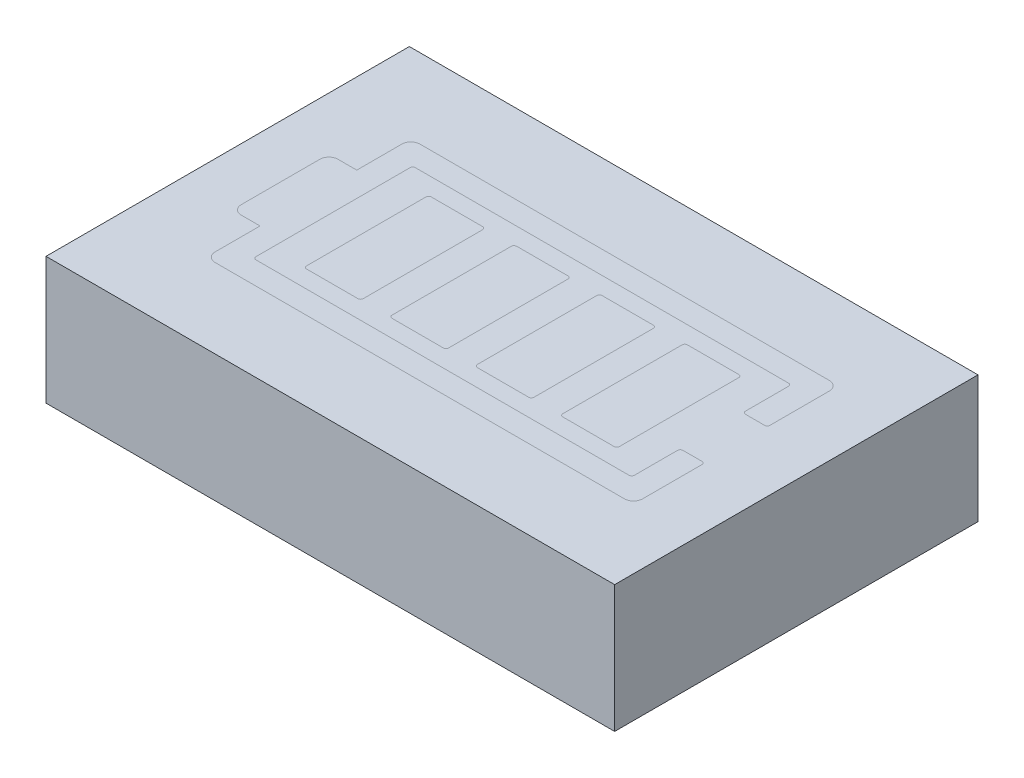
SolidWorks part; units mm, degrees
ref_plane "Front Plane" through (0, 0, 0) normal (0, 0, 1) x (1, 0, 0)
ref_plane "Top Plane" through (0, 0, 0) normal (0, 1, 0) x (1, 0, 0)
ref_plane "Right Plane" through (0, 0, 0) normal (1, 0, 0) x (0, 0, -1)
sketch "Sketch1" plane through (0, 0, 0) normal (0, 1, 0) x (1, 0, 0)
  line L0 (-14.65, -9) -> (-14.65, 9)
  line L1 (-15.65, -10) -> (15.65, -10)
  line L2 (-15.65, -10) -> (-15.65, 10)
  line L3 (-15.65, 10) -> (15.65, 10)
  line L4 (15.65, -10) -> (15.65, 10)
  line L5 (-15.65, -10) -> (15.65, 10) construction
  line L6 (-15.65, 10) -> (15.65, -10) construction
  line L7 (-14.65, 9) -> (-7, 9)
  line L8 (14.65, -9) -> (14.65, 9)
  line L9 (-14.65, -9) -> (-7, -9)
  line L10 (-7, 7) -> (-6, 7)
  line L12 (-7, 9) -> (-7, 7)
  line L14 (-6, 9) -> (-6, 7)
  line L15 (-7, 9) -> (-6.8889, 7) construction
  line L16 (-7, -9) -> (-6.8889, -7) construction
  line L17 (0, -9) -> (0, 9) construction
  line L18 (-14.65, 0) -> (14.65, 0) construction
  line L19 (-7, -7) -> (-6, -7)
  line L20 (-7, -7) -> (-7, -9)
  line L21 (-6.1111, -7) -> (-6, -9) construction
  line L22 (-6.1111, 7) -> (-6, 9) construction
  line L23 (-6, -7) -> (-6, -9)
  line L24 (-6, 9) -> (6, 9)
  line L25 (-14.65, 9) -> (14.65, 9) construction
  line L26 (-6, -9) -> (6, -9)
  line L27 (-14.65, -9) -> (14.65, -9) construction
  line L28 (6.1111, -7) -> (6, -9) construction
  line L29 (7, -9) -> (6.8889, -7) construction
  line L30 (6, -7) -> (6, -9)
  line L31 (7, -7) -> (7, -9)
  line L32 (7, -7) -> (6, -7)
  line L33 (6.1111, 7) -> (6, 9) construction
  line L34 (7, 9) -> (6.8889, 7) construction
  line L35 (6, 9) -> (6, 7)
  line L36 (7, 9) -> (7, 7)
  line L37 (7, 7) -> (6, 7)
  line L38 (7, 9) -> (14.65, 9)
  line L39 (7, -9) -> (14.65, -9)
  point P0 (0, 0)
  point P14 (-6.5, 0)
  point P20 (0, 0)
  point P23 (0, 0)
  dimension "D1" = 20
  dimension "D2" = 31.3
  dimension "D4" = 1
  dimension "D5" = 6
  dimension "D6" = 2
  dimension "D3" = 1
extrude "Boss-Extrude1" add sketch "Sketch1" along normal blind 7
sketch "Sketch2" plane through (0, 7, 0) normal (0, 1, 0) x (1, 0, 0)
  line L0 (15.65, -10) -> (15.65, 10) construction
  line L1 (-15.65, -10) -> (15.65, -10) construction
  line L2 (-15.65, 10) -> (-15.65, -10) construction
  line L3 (15.65, 10) -> (-15.65, 10) construction
  line L4 (15.65, -10) -> (15.65, 10)
  line L5 (-15.65, -10) -> (15.65, -10)
  line L6 (-15.65, 10) -> (-15.65, -10)
  line L7 (15.65, 10) -> (-15.65, 10)
extrude "Boss-Extrude2" add sketch "Sketch2" against normal blind 1
sketch "Sketch3" plane through (0, 0, 0) normal (0, -1, 0) x (1, 0, 0)
  line L0 (-14.65, -9) -> (-14.65, 9) construction
  line L1 (-14.65, -9) -> (-14.65, 9)
  line L2 (14.65, 9) -> (14.65, -9) construction
  line L3 (14.65, 9) -> (14.65, -9)
  line L4 (-14.65, 9) -> (14.65, 9)
  line L5 (-14.65, -9) -> (14.65, -9)
extrude "Boss-Extrude4" add sketch "Sketch3" against normal up to surface (5.75 mm away) from offset 0.25 up to face at (0, 6, 0) offset against normal yes
sketch "Sketch4" plane through (0, 7, 0) normal (0, 1, 0) x (1, 0, 0)
  line L0 (15.65, 0) -> (-4.9013, 0) construction
  line L1 (15.65, -10) -> (15.65, 10) construction
  line L2 (-15.65, 10) -> (-15.65, -10) construction
  line L3 (-9.8559, 4.2413) -> (-9.8559, -4.2413)
  line L4 (-9.7059, 4.3913) -> (10.8308, 4.3913)
  line L5 (10.9808, 4.2413) -> (10.9808, 1.8698)
  line L6 (11.1308, 1.7198) -> (12.1808, 1.7198)
  line L7 (12.3308, 1.8698) -> (12.3308, 5.1413)
  line L8 (11.8308, 5.6413) -> (-10.7059, 5.6413)
  line L9 (-11.2059, 5.1413) -> (-11.2059, 2.6617)
  line L10 (-11.2059, 2.6617) -> (-12.24, 2.6617)
  line L11 (-12.74, 2.1617) -> (-12.74, -2.1617)
  line L12 (-11.2059, -2.6617) -> (-12.24, -2.6617)
  line L13 (-11.2059, -5.1413) -> (-11.2059, -2.6617)
  line L14 (11.8308, -5.6413) -> (-10.7059, -5.6413)
  line L15 (12.3308, -1.8698) -> (12.3308, -5.1413)
  line L16 (11.1308, -1.7198) -> (12.1808, -1.7198)
  line L17 (10.9808, -4.2413) -> (10.9808, -1.8698)
  line L18 (-9.7059, -4.3913) -> (10.8308, -4.3913)
  line L19 (-8.0236, 0) -> (-15.65, 0) construction
  line L20 (-7.8736, 3.4332) -> (-5.0513, 3.4332)
  line L21 (-8.0236, 3.2832) -> (-8.0236, -3.2832)
  line L23 (-4.9013, 3.2832) -> (-4.9013, -3.2832)
  line L24 (-8.0236, 3.4332) -> (-4.9013, 0) construction
  line L25 (-8.0236, 0) -> (-4.9013, 3.4332) construction
  line L26 (-0.2013, 3.2832) -> (-0.2013, -3.2832)
  line L27 (-3.3236, 0) -> (-0.2013, 3.4332) construction
  line L28 (-3.3236, 3.4332) -> (-0.2013, 0) construction
  line L29 (-3.3236, 3.2832) -> (-3.3236, -3.2832)
  line L30 (-3.1736, 3.4332) -> (-0.3513, 3.4332)
  line L31 (4.4987, 3.2832) -> (4.4987, -3.2832)
  line L32 (1.3764, 0) -> (4.4987, 3.4332) construction
  line L33 (1.3764, 3.4332) -> (4.4987, 0) construction
  line L34 (1.3764, 3.2832) -> (1.3764, -3.2832)
  line L35 (1.5264, 3.4332) -> (4.3487, 3.4332)
  line L36 (9.1987, 3.2832) -> (9.1987, -3.2832)
  line L37 (6.0764, 0) -> (9.1987, 3.4332) construction
  line L38 (6.0764, 3.4332) -> (9.1987, 0) construction
  line L39 (6.0764, 3.2832) -> (6.0764, -3.2832)
  line L40 (6.2264, 3.4332) -> (9.0487, 3.4332)
  line L41 (6.0764, -3.4332) -> (9.1987, 0) construction
  line L42 (6.0764, 0) -> (9.1987, -3.4332) construction
  line L43 (1.3764, -3.4332) -> (4.4987, 0) construction
  line L44 (1.3764, 0) -> (4.4987, -3.4332) construction
  line L45 (-3.3236, -3.4332) -> (-0.2013, 0) construction
  line L46 (-3.3236, 0) -> (-0.2013, -3.4332) construction
  line L47 (-8.0236, 0) -> (-4.9013, -3.4332) construction
  line L48 (-8.0236, -3.4332) -> (-4.9013, 0) construction
  line L49 (6.2264, -3.4332) -> (9.0487, -3.4332)
  line L50 (1.5264, -3.4332) -> (4.3487, -3.4332)
  line L51 (-3.1736, -3.4332) -> (-0.3513, -3.4332)
  line L52 (-7.8736, -3.4332) -> (-5.0513, -3.4332)
  arc A0 (10.8308, 4.3913) -> (10.9808, 4.2413) centre (10.8308, 4.2413) cw
  arc A1 (-9.8559, 4.2413) -> (-9.7059, 4.3913) centre (-9.7059, 4.2413) cw
  arc A2 (-12.24, 2.6617) -> (-12.74, 2.1617) centre (-12.24, 2.1617) ccw
  arc A3 (12.3308, 5.1413) -> (11.8308, 5.6413) centre (11.8308, 5.1413) ccw
  arc A4 (-10.7059, 5.6413) -> (-11.2059, 5.1413) centre (-10.7059, 5.1413) ccw
  arc A5 (12.1808, 1.7198) -> (12.3308, 1.8698) centre (12.1808, 1.8698) ccw
  arc A6 (10.9808, 1.8698) -> (11.1308, 1.7198) centre (11.1308, 1.8698) ccw
  arc A7 (10.9808, -1.8698) -> (11.1308, -1.7198) centre (11.1308, -1.8698) cw
  arc A8 (12.1808, -1.7198) -> (12.3308, -1.8698) centre (12.1808, -1.8698) cw
  arc A9 (-10.7059, -5.6413) -> (-11.2059, -5.1413) centre (-10.7059, -5.1413) cw
  arc A10 (12.3308, -5.1413) -> (11.8308, -5.6413) centre (11.8308, -5.1413) cw
  arc A11 (-12.24, -2.6617) -> (-12.74, -2.1617) centre (-12.24, -2.1617) cw
  arc A12 (-9.8559, -4.2413) -> (-9.7059, -4.3913) centre (-9.7059, -4.2413) ccw
  arc A13 (10.8308, -4.3913) -> (10.9808, -4.2413) centre (10.8308, -4.2413) ccw
  arc A14 (-5.0513, 3.4332) -> (-4.9013, 3.2832) centre (-5.0513, 3.2832) cw
  arc A15 (-7.8736, 3.4332) -> (-8.0236, 3.2832) centre (-7.8736, 3.2832) ccw
  arc A16 (-0.3513, 3.4332) -> (-0.2013, 3.2832) centre (-0.3513, 3.2832) cw
  arc A17 (-3.1736, 3.4332) -> (-3.3236, 3.2832) centre (-3.1736, 3.2832) ccw
  arc A18 (4.3487, 3.4332) -> (4.4987, 3.2832) centre (4.3487, 3.2832) cw
  arc A19 (1.5264, 3.4332) -> (1.3764, 3.2832) centre (1.5264, 3.2832) ccw
  arc A20 (9.0487, 3.4332) -> (9.1987, 3.2832) centre (9.0487, 3.2832) cw
  arc A21 (6.2264, 3.4332) -> (6.0764, 3.2832) centre (6.2264, 3.2832) ccw
  arc A22 (6.2264, -3.4332) -> (6.0764, -3.2832) centre (6.2264, -3.2832) cw
  arc A23 (9.0487, -3.4332) -> (9.1987, -3.2832) centre (9.0487, -3.2832) ccw
  arc A24 (1.5264, -3.4332) -> (1.3764, -3.2832) centre (1.5264, -3.2832) cw
  arc A25 (4.3487, -3.4332) -> (4.4987, -3.2832) centre (4.3487, -3.2832) ccw
  arc A26 (-3.1736, -3.4332) -> (-3.3236, -3.2832) centre (-3.1736, -3.2832) cw
  arc A27 (-0.3513, -3.4332) -> (-0.2013, -3.2832) centre (-0.3513, -3.2832) ccw
  arc A28 (-7.8736, -3.4332) -> (-8.0236, -3.2832) centre (-7.8736, -3.2832) cw
  arc A29 (-5.0513, -3.4332) -> (-4.9013, -3.2832) centre (-5.0513, -3.2832) ccw
  point P9 (-9.8559, 0)
  point P52 (-12.74, 0)
  point P53 (-9.8559, 0)
  point P57 (-6.4624, 1.7166)
  point P126 (-6.4624, -1.7166)
  dimension "D4" = 0.15
  dimension "D5" = 0.5
  dimension "D6" = 0.15
  dimension "D7" = 0.15
  dimension "D1" = 1.35
  dimension "D2" = 1.25
  dimension "D3" = 1.35
  dimension "D8" = 4
ref_plane "Plane1" through (0, 17, 0) normal (0, 1, 0) x (1, 0, 0)
sketch "Sketch5" plane through (0, 17, 0) normal (0, 1, 0) x (1, 0, 0)
  line L0 (1.5264, -3.4332) -> (4.3487, -3.4332) construction
  line L1 (4.4987, 3.2832) -> (4.4987, -3.2832) construction
  line L2 (1.3764, 3.2832) -> (1.3764, -3.2832) construction
  line L3 (1.5264, 3.4332) -> (4.3487, 3.4332) construction
  line L4 (-3.1736, -3.4332) -> (-0.3513, -3.4332) construction
  line L5 (-0.2013, 3.2832) -> (-0.2013, -3.2832) construction
  line L6 (-3.3236, 3.2832) -> (-3.3236, -3.2832) construction
  line L7 (-3.1736, 3.4332) -> (-0.3513, 3.4332) construction
  line L8 (6.2264, -3.4332) -> (9.0487, -3.4332) construction
  line L9 (6.0764, 3.2832) -> (6.0764, -3.2832) construction
  line L10 (9.1987, 3.2832) -> (9.1987, -3.2832) construction
  line L11 (6.2264, 3.4332) -> (9.0487, 3.4332) construction
  line L12 (12.3308, -1.8698) -> (12.3308, -5.1413) construction
  line L13 (11.1308, -1.7198) -> (12.1808, -1.7198) construction
  line L14 (10.9808, -4.2413) -> (10.9808, -1.8698) construction
  line L15 (11.1308, 1.7198) -> (12.1808, 1.7198) construction
  line L16 (10.9808, 4.2413) -> (10.9808, 1.8698) construction
  line L17 (12.3308, 1.8698) -> (12.3308, 5.1413) construction
  line L18 (-4.9013, 3.2832) -> (-4.9013, -3.2832) construction
  line L19 (-7.8736, -3.4332) -> (-5.0513, -3.4332) construction
  line L20 (-9.7059, -4.3913) -> (10.8308, -4.3913) construction
  line L21 (11.8308, -5.6413) -> (-10.7059, -5.6413) construction
  line L22 (-11.2059, -5.1413) -> (-11.2059, -2.6617) construction
  line L23 (-11.2059, -2.6617) -> (-12.24, -2.6617) construction
  line L24 (-8.0236, 3.2832) -> (-8.0236, -3.2832) construction
  line L25 (-7.8736, 3.4332) -> (-5.0513, 3.4332) construction
  line L26 (-9.7059, 4.3913) -> (10.8308, 4.3913) construction
  line L27 (-9.8559, 4.2413) -> (-9.8559, -4.2413) construction
  line L28 (-12.74, 2.1617) -> (-12.74, -2.1617) construction
  line L29 (-11.2059, 2.6617) -> (-12.24, 2.6617) construction
  line L30 (-11.2059, 5.1413) -> (-11.2059, 2.6617) construction
  line L31 (11.8308, 5.6413) -> (-10.7059, 5.6413) construction
  line L32 (1.5264, -3.4332) -> (4.3487, -3.4332)
  line L33 (4.4987, 3.2832) -> (4.4987, -3.2832)
  line L34 (1.3764, 3.2832) -> (1.3764, -3.2832)
  line L35 (1.5264, 3.4332) -> (4.3487, 3.4332)
  line L36 (-3.1736, -3.4332) -> (-0.3513, -3.4332)
  line L37 (-0.2013, 3.2832) -> (-0.2013, -3.2832)
  line L38 (-3.3236, 3.2832) -> (-3.3236, -3.2832)
  line L39 (-3.1736, 3.4332) -> (-0.3513, 3.4332)
  line L40 (6.2264, -3.4332) -> (9.0487, -3.4332)
  line L41 (6.0764, 3.2832) -> (6.0764, -3.2832)
  line L42 (9.1987, 3.2832) -> (9.1987, -3.2832)
  line L43 (6.2264, 3.4332) -> (9.0487, 3.4332)
  line L44 (12.3308, -1.8698) -> (12.3308, -5.1413)
  line L45 (11.1308, -1.7198) -> (12.1808, -1.7198)
  line L46 (10.9808, -4.2413) -> (10.9808, -1.8698)
  line L47 (11.1308, 1.7198) -> (12.1808, 1.7198)
  line L48 (10.9808, 4.2413) -> (10.9808, 1.8698)
  line L49 (12.3308, 1.8698) -> (12.3308, 5.1413)
  line L50 (-4.9013, 3.2832) -> (-4.9013, -3.2832)
  line L51 (-7.8736, -3.4332) -> (-5.0513, -3.4332)
  line L52 (-9.7059, -4.3913) -> (10.8308, -4.3913)
  line L53 (11.8308, -5.6413) -> (-10.7059, -5.6413)
  line L54 (-11.2059, -5.1413) -> (-11.2059, -2.6617)
  line L55 (-11.2059, -2.6617) -> (-12.24, -2.6617)
  line L56 (-8.0236, 3.2832) -> (-8.0236, -3.2832)
  line L57 (-7.8736, 3.4332) -> (-5.0513, 3.4332)
  line L58 (-9.7059, 4.3913) -> (10.8308, 4.3913)
  line L59 (-9.8559, 4.2413) -> (-9.8559, -4.2413)
  line L60 (-12.74, 2.1617) -> (-12.74, -2.1617)
  line L61 (-11.2059, 2.6617) -> (-12.24, 2.6617)
  line L62 (-11.2059, 5.1413) -> (-11.2059, 2.6617)
  line L63 (11.8308, 5.6413) -> (-10.7059, 5.6413)
  arc A0 (4.3487, -3.4332) -> (4.4987, -3.2832) centre (4.3487, -3.2832) ccw construction
  arc A1 (1.3764, -3.2832) -> (1.5264, -3.4332) centre (1.5264, -3.2832) ccw construction
  arc A2 (4.4987, 3.2832) -> (4.3487, 3.4332) centre (4.3487, 3.2832) ccw construction
  arc A3 (1.5264, 3.4332) -> (1.3764, 3.2832) centre (1.5264, 3.2832) ccw construction
  arc A4 (-0.3513, -3.4332) -> (-0.2013, -3.2832) centre (-0.3513, -3.2832) ccw construction
  arc A5 (-3.3236, -3.2832) -> (-3.1736, -3.4332) centre (-3.1736, -3.2832) ccw construction
  arc A6 (-3.1736, 3.4332) -> (-3.3236, 3.2832) centre (-3.1736, 3.2832) ccw construction
  arc A7 (-0.2013, 3.2832) -> (-0.3513, 3.4332) centre (-0.3513, 3.2832) ccw construction
  arc A8 (9.0487, -3.4332) -> (9.1987, -3.2832) centre (9.0487, -3.2832) ccw construction
  arc A9 (6.0764, -3.2832) -> (6.2264, -3.4332) centre (6.2264, -3.2832) ccw construction
  arc A10 (6.2264, 3.4332) -> (6.0764, 3.2832) centre (6.2264, 3.2832) ccw construction
  arc A11 (9.1987, 3.2832) -> (9.0487, 3.4332) centre (9.0487, 3.2832) ccw construction
  arc A12 (11.8308, -5.6413) -> (12.3308, -5.1413) centre (11.8308, -5.1413) ccw construction
  arc A13 (12.3308, -1.8698) -> (12.1808, -1.7198) centre (12.1808, -1.8698) ccw construction
  arc A14 (11.1308, -1.7198) -> (10.9808, -1.8698) centre (11.1308, -1.8698) ccw construction
  arc A15 (10.8308, -4.3913) -> (10.9808, -4.2413) centre (10.8308, -4.2413) ccw construction
  arc A16 (12.1808, 1.7198) -> (12.3308, 1.8698) centre (12.1808, 1.8698) ccw construction
  arc A17 (10.9808, 1.8698) -> (11.1308, 1.7198) centre (11.1308, 1.8698) ccw construction
  arc A18 (12.3308, 5.1413) -> (11.8308, 5.6413) centre (11.8308, 5.1413) ccw construction
  arc A19 (10.9808, 4.2413) -> (10.8308, 4.3913) centre (10.8308, 4.2413) ccw construction
  arc A20 (-5.0513, -3.4332) -> (-4.9013, -3.2832) centre (-5.0513, -3.2832) ccw construction
  arc A21 (-4.9013, 3.2832) -> (-5.0513, 3.4332) centre (-5.0513, 3.2832) ccw construction
  arc A22 (-8.0236, -3.2832) -> (-7.8736, -3.4332) centre (-7.8736, -3.2832) ccw construction
  arc A23 (-11.2059, -5.1413) -> (-10.7059, -5.6413) centre (-10.7059, -5.1413) ccw construction
  arc A24 (-9.8559, -4.2413) -> (-9.7059, -4.3913) centre (-9.7059, -4.2413) ccw construction
  arc A25 (-12.74, -2.1617) -> (-12.24, -2.6617) centre (-12.24, -2.1617) ccw construction
  arc A26 (-7.8736, 3.4332) -> (-8.0236, 3.2832) centre (-7.8736, 3.2832) ccw construction
  arc A27 (-9.7059, 4.3913) -> (-9.8559, 4.2413) centre (-9.7059, 4.2413) ccw construction
  arc A28 (-12.24, 2.6617) -> (-12.74, 2.1617) centre (-12.24, 2.1617) ccw construction
  arc A29 (-10.7059, 5.6413) -> (-11.2059, 5.1413) centre (-10.7059, 5.1413) ccw construction
  arc A30 (4.3487, -3.4332) -> (4.4987, -3.2832) centre (4.3487, -3.2832) ccw
  arc A31 (1.3764, -3.2832) -> (1.5264, -3.4332) centre (1.5264, -3.2832) ccw
  arc A32 (4.4987, 3.2832) -> (4.3487, 3.4332) centre (4.3487, 3.2832) ccw
  arc A33 (1.5264, 3.4332) -> (1.3764, 3.2832) centre (1.5264, 3.2832) ccw
  arc A34 (-0.3513, -3.4332) -> (-0.2013, -3.2832) centre (-0.3513, -3.2832) ccw
  arc A35 (-3.3236, -3.2832) -> (-3.1736, -3.4332) centre (-3.1736, -3.2832) ccw
  arc A36 (-3.1736, 3.4332) -> (-3.3236, 3.2832) centre (-3.1736, 3.2832) ccw
  arc A37 (-0.2013, 3.2832) -> (-0.3513, 3.4332) centre (-0.3513, 3.2832) ccw
  arc A38 (9.0487, -3.4332) -> (9.1987, -3.2832) centre (9.0487, -3.2832) ccw
  arc A39 (6.0764, -3.2832) -> (6.2264, -3.4332) centre (6.2264, -3.2832) ccw
  arc A40 (6.2264, 3.4332) -> (6.0764, 3.2832) centre (6.2264, 3.2832) ccw
  arc A41 (9.1987, 3.2832) -> (9.0487, 3.4332) centre (9.0487, 3.2832) ccw
  arc A42 (11.8308, -5.6413) -> (12.3308, -5.1413) centre (11.8308, -5.1413) ccw
  arc A43 (12.3308, -1.8698) -> (12.1808, -1.7198) centre (12.1808, -1.8698) ccw
  arc A44 (11.1308, -1.7198) -> (10.9808, -1.8698) centre (11.1308, -1.8698) ccw
  arc A45 (10.8308, -4.3913) -> (10.9808, -4.2413) centre (10.8308, -4.2413) ccw
  arc A46 (12.1808, 1.7198) -> (12.3308, 1.8698) centre (12.1808, 1.8698) ccw
  arc A47 (10.9808, 1.8698) -> (11.1308, 1.7198) centre (11.1308, 1.8698) ccw
  arc A48 (12.3308, 5.1413) -> (11.8308, 5.6413) centre (11.8308, 5.1413) ccw
  arc A49 (10.9808, 4.2413) -> (10.8308, 4.3913) centre (10.8308, 4.2413) ccw
  arc A50 (-5.0513, -3.4332) -> (-4.9013, -3.2832) centre (-5.0513, -3.2832) ccw
  arc A51 (-4.9013, 3.2832) -> (-5.0513, 3.4332) centre (-5.0513, 3.2832) ccw
  arc A52 (-8.0236, -3.2832) -> (-7.8736, -3.4332) centre (-7.8736, -3.2832) ccw
  arc A53 (-11.2059, -5.1413) -> (-10.7059, -5.6413) centre (-10.7059, -5.1413) ccw
  arc A54 (-9.8559, -4.2413) -> (-9.7059, -4.3913) centre (-9.7059, -4.2413) ccw
  arc A55 (-12.74, -2.1617) -> (-12.24, -2.6617) centre (-12.24, -2.1617) ccw
  arc A56 (-7.8736, 3.4332) -> (-8.0236, 3.2832) centre (-7.8736, 3.2832) ccw
  arc A57 (-9.7059, 4.3913) -> (-9.8559, 4.2413) centre (-9.7059, 4.2413) ccw
  arc A58 (-12.24, 2.6617) -> (-12.74, 2.1617) centre (-12.24, 2.1617) ccw
  arc A59 (-10.7059, 5.6413) -> (-11.2059, 5.1413) centre (-10.7059, 5.1413) ccw
split line "Split Line1"
